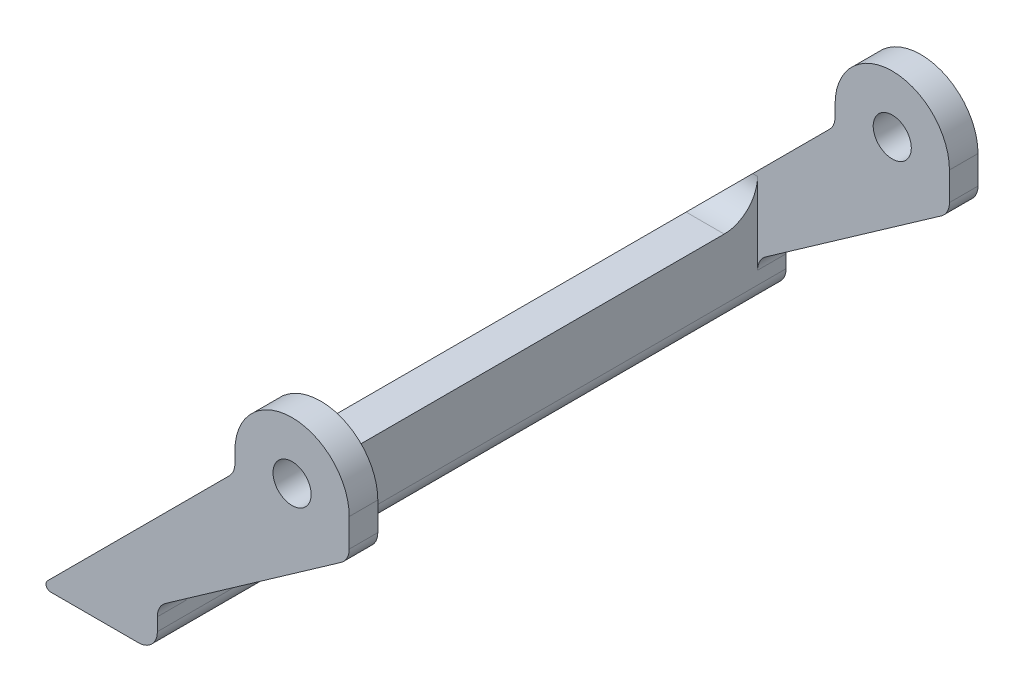
SolidWorks part; units mm, degrees
ref_plane "Front Plane" through (0, 0, 0) normal (0, 0, 1) x (1, 0, 0)
ref_plane "Top Plane" through (0, 0, 0) normal (0, 1, 0) x (1, 0, 0)
ref_plane "Right Plane" through (0, 0, 0) normal (1, 0, 0) x (0, 0, -1)
sketch "Sketch1" plane through (0, 0, 0) normal (0, 0, 1) x (1, 0, 0)
  line L0 (-14.8033, -5.2013) -> (-2.6633, 6.9387)
  line L1 (-10.8033, -5.2013) -> (-14.8033, -5.2013)
  line L2 (-2.6633, 6.9387) -> (-2.6633, 8.9408)
  line L3 (9.3367, 4.9408) -> (-10.8033, -9.2013)
  line L5 (9.3367, 4.9408) -> (9.3367, 8.9408)
  line L6 (-10.8033, -5.2013) -> (-10.8033, -9.2013)
  arc A0 (-2.6633, 8.9408) -> (9.3367, 8.9408) centre (3.3367, 8.9408) cw
  dimension "D4" = 18.1421
  dimension "D1" = 45
  dimension "D6" = 14.14
  dimension "D5" = 6
  dimension "D2" = 4
  dimension "D3" = 12
  dimension "D7" = 4
  dimension "D8" = 4
extrude "Extrude1" add sketch "Sketch1" along normal blind 3
sketch "Sketch3" plane through (0, 0, 0) normal (0, 0, 1) x (1, 0, 0)
  line L0 (-14.8033, -5.2013) -> (-10.8033, -5.2013)
  line L1 (-10.8033, -5.2013) -> (-10.8033, -13.5962)
  line L2 (-10.8033, -13.5962) -> (-23.1982, -13.5962)
  line L3 (-23.1982, -13.5962) -> (-14.8033, -5.2013)
  dimension "D1" = 8.3949
  dimension "D2" = 45
extrude "Extrude2" add sketch "Sketch3" along normal blind 66
sketch "Sketch4" plane through (0, 0, 66) normal (0, 0, 1) x (1, 0, 0)
  line L0 (-14.8033, -5.2013) -> (-10.8033, -5.2013)
  line L1 (-10.8033, -5.2013) -> (-10.8033, -9.2013)
  line L2 (-10.8033, -9.2013) -> (9.3367, 4.9408)
  line L3 (9.3367, 4.9408) -> (9.3367, 8.9408)
  line L4 (-14.8033, -5.2013) -> (-2.6633, 6.9387)
  line L5 (-2.6633, 6.9387) -> (-2.6633, 8.9408)
  line L6 (-10.8033, -13.5962) -> (-10.8033, -5.2013) construction
  line L8 (-10.8033, -9.2013) -> (9.3367, 4.9408) construction
  arc A0 (-2.6633, 8.9408) -> (9.3367, 8.9408) centre (3.3367, 8.9408) cw
extrude "Extrude3" add sketch "Sketch4" against normal blind 3
sketch "Sketch2" plane through (0, 0, 3) normal (0, 0, 1) x (1, 0, 0)
  circle A0 centre (3.3367, 8.9408) radius 2
extrude "Extrude4" cut sketch "Sketch2" against normal up to surface (3 mm away) up to face at (-4.494, -0.0904, 0)
sketch "Sketch6" plane through (0, 0, 63) normal (0, 0, -1) x (-1, 0, 0)
  circle A0 centre (-3.3367, 8.9408) radius 2
  dimension "D1" = 4
extrude "Extrude5" cut sketch "Sketch6" against normal up to surface (3 mm away) up to face at (-4.494, -0.0904, 66)
fillet "Fillet3" radius 3.5 2 edges at (-12.8033, -5.2013, 63) (-12.8033, -5.2013, 3)
fillet "Fillet6" radius 2 4 edges at (-2.6633, 6.9387, 1.5) (-2.6633, 6.9387, 64.5) (9.3367, 4.9408, 1.5) (9.3367, 4.9408, 64.5)
fillet "Fillet7" radius 0.5 1 edges at (-23.1982, -13.5962, 33)
fillet "Fillet13" radius 2 3 edges at (-10.8033, -13.5962, 33) (-10.8033, -9.2013, 1.5) (-10.8033, -9.2013, 64.5)
